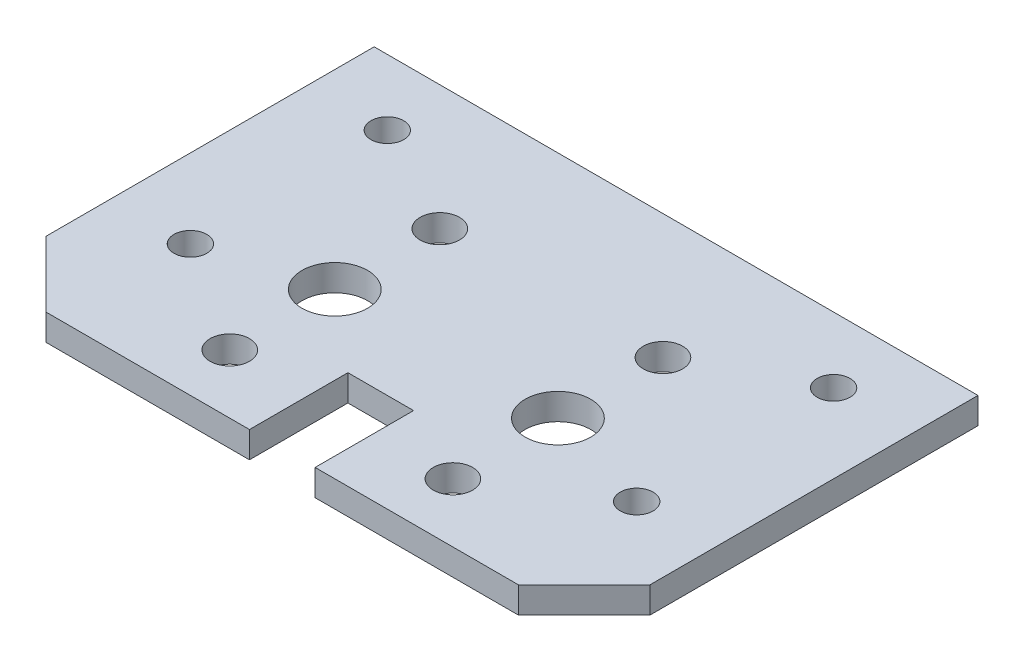
SolidWorks part; units mm, degrees
ref_plane "Спереди" through (0, 0, 0) normal (0, 0, 1) x (1, 0, 0)
ref_plane "Сверху" through (0, 0, 0) normal (0, 1, 0) x (1, 0, 0)
ref_plane "Справа" through (0, 0, 0) normal (1, 0, 0) x (0, 0, -1)
sketch "Эскиз1" plane through (0, 0, 0) normal (0, 1, 0) x (1, 0, 0)
  line L0 (12, 60) -> (12, 0) construction
  line L1 (0, 0) -> (92, 0)
  line L2 (0, 0) -> (0, 60)
  line L3 (0, 60) -> (92, 60)
  line L4 (92, 0) -> (92, 60)
  line L5 (80, 60) -> (80, 0) construction
  line L6 (29, 25) -> (63, 25) construction
  line L7 (46, 60) -> (46, 0) construction
  line L8 (29, 38.1007) -> (29, 6.4976) construction
  line L9 (63, 43.8556) -> (63, 6.4976) construction
  circle A0 centre (12, 50) radius 2.5
  circle A2 centre (12, 20) radius 2.5
  circle A3 centre (80, 50) radius 2.5
  circle A5 centre (80, 20) radius 2.5
  circle A6 centre (29, 25) radius 5
  circle A7 centre (63, 25) radius 5
  circle A8 centre (29, 41) radius 3
  circle A9 centre (29, 9) radius 3
  circle A10 centre (63, 41) radius 3
  circle A11 centre (63, 9) radius 3
  dimension "D5" = 5
  dimension "D7" = 5
  dimension "D12" = 10
  dimension "D13" = 10
  dimension "D17" = 6
  dimension "D18" = 6
  dimension "D19" = 6
  dimension "D20" = 6
  dimension "D1" = 92
  dimension "D2" = 60
  dimension "D3" = 34
  dimension "D4" = 34
  dimension "D8" = 10
  dimension "D14" = 17
  dimension "D15" = 17
  dimension "D16" = 35
  dimension "D21" = 16
  dimension "D22" = 16
  dimension "D23" = 16
  dimension "D24" = 16
  dimension "D11" = 2
extrude "Бобышка-Вытянуть1" add sketch "Эскиз1" along normal blind 4
sketch "Эскиз2" plane through (0, 4, 0) normal (0, 1, 0) x (1, 0, 0)
  line L0 (46, 60) -> (46, 0) construction
  line L1 (92, 60) -> (0, 60) construction
  line L2 (0, 0) -> (92, 0) construction
  line L4 (41, 0) -> (51, 0)
  line L5 (41, 0) -> (41, 15)
  line L6 (41, 15) -> (51, 15)
  line L7 (51, 0) -> (51, 15)
  dimension "D1" = 10
  dimension "D2" = 15
extrude "Вырез-Вытянуть1" cut sketch "Эскиз2" against normal blind 10
sketch "Эскиз3" plane through (0, 4, 0) normal (0, 1, 0) x (1, 0, 0)
  line L0 (10, 0) -> (0, 10)
  line L1 (0, 60) -> (0, 0) construction
  line L2 (0, 10) -> (0, 0)
  line L3 (0, 0) -> (10, 0)
  line L4 (92, 0) -> (92, 10)
  line L5 (92, 0) -> (92, 60) construction
  line L6 (92, 10) -> (82, 0)
  line L7 (51, 0) -> (92, 0) construction
  line L8 (82, 0) -> (92, 0)
  dimension "D1" = 10
extrude "Вырез-Вытянуть2" cut sketch "Эскиз3" against normal blind 4
